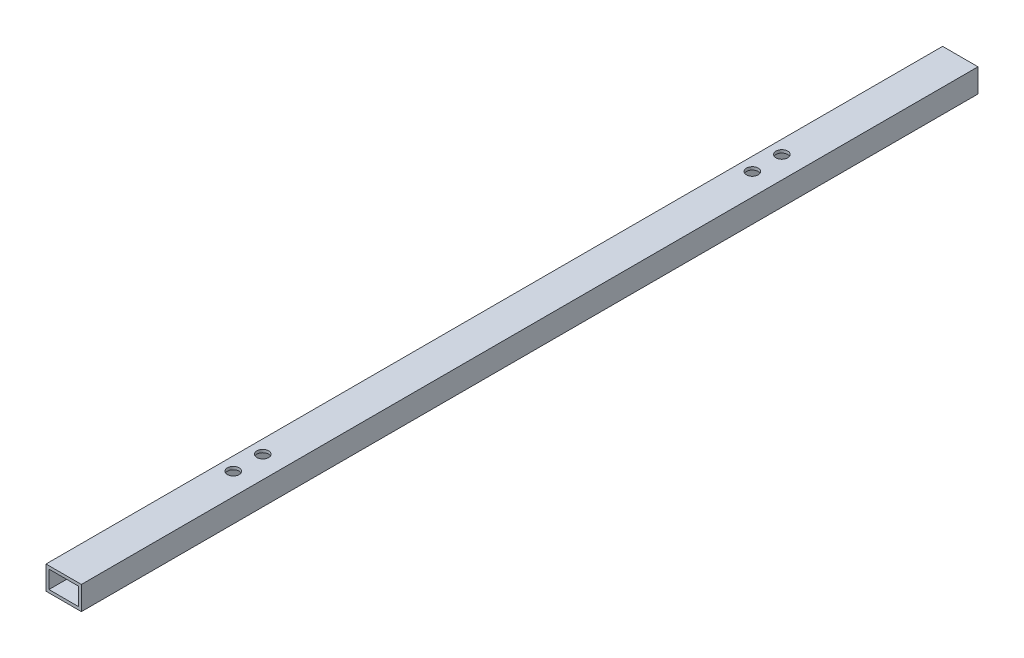
SolidWorks part; units mm, degrees
material "6061 Alloy"
ref_plane "Front Plane" through (0, 0, 0) normal (0, 0, 1) x (1, 0, 0)
ref_plane "Top Plane" through (0, 0, 0) normal (0, 1, 0) x (1, 0, 0)
ref_plane "Right Plane" through (0, 0, 0) normal (1, 0, 0) x (0, 0, -1)
sketch "Sketch1" plane through (0, 0, 0) normal (0, 0, 1) x (1, 0, 0)
  line L0 (19.05, 0) -> (15.875, 0) construction
  line L1 (-19.05, 0) -> (19.05, 0) construction
  line L2 (0, 12.7) -> (0, -12.7)
  point P7 (0, 0)
sketch "Sketch2" plane through (0, 0, 0) normal (1, 0, 0) x (0, 0, -1)
  line L0 (482.6, 0) -> (-482.6, 0)
  point P4 (0, 0)
  dimension "Length" = 965.2
sketch "Sketch3" plane through (0, 0, 0) normal (0, 0, 1) x (1, 0, 0)
  line L0 (-19.05, 0) -> (19.05, 0) construction
  line L5 (19.05, -12.7) -> (-19.05, -12.7)
  line L6 (19.05, -12.7) -> (19.05, 12.7)
  line L11 (19.05, 12.7) -> (-19.05, 12.7)
  line L12 (-19.05, -12.7) -> (-19.05, 12.7)
  line L14 (19.05, -12.7) -> (-19.05, 12.7) construction
  line L15 (19.05, 12.7) -> (-19.05, -12.7) construction
  line L16 (15.875, -9.525) -> (-15.875, -9.525)
  line L17 (15.875, -9.525) -> (15.875, 9.525)
  line L18 (15.875, 9.525) -> (-15.875, 9.525)
  line L19 (-15.875, -9.525) -> (-15.875, 9.525)
  line L20 (15.875, -9.525) -> (-15.875, 9.525) construction
  line L21 (15.875, 9.525) -> (-15.875, -9.525) construction
  point P0 (0, 0)
  point P5 (0, 0)
  point P13 (15.875, -12.7)
  dimension "D1" = 3.175
  dimension "D3" = 38.1
  dimension "D4" = 25.4
  dimension "D2" = 3.175
extrude "Boss-Extrude1" add sketch "Sketch3" along normal up to vertex (482.6 mm away) and the other way up to vertex (482.6 mm away) up to point (0, 0, 482.6) other way up to point (0, 0, -482.6)
sketch "Sketch5" plane through (0, 0, 0) normal (1, 0, 0) x (0, 0, -1)
  line L0 (-482.6, 0) -> (482.6, 0) construction
  line L3 (-482.6, -12.7) -> (-482.6, 12.7) construction
  line L4 (482.6, -12.7) -> (482.6, 12.7) construction
  point P6 (-439.7375, 0)
  point P7 (-425.45, 0)
  point P8 (425.45, 0)
  point P10 (439.7375, 0)
  dimension "D1" = 42.8625
  dimension "D2" = 57.15
  dimension "D3" = 42.8625
  dimension "D4" = 57.15
sketch "Sketch6" plane through (0, 12.7, 0) normal (0, 1, 0) x (1, 0, 0)
  line L0 (19.05, 482.6) -> (-19.05, 482.6) construction
  line L1 (-19.05, 0) -> (19.05, 0) construction
  line L2 (-19.05, -482.6) -> (-19.05, 482.6) construction
  line L3 (19.05, -482.6) -> (19.05, 482.6) construction
  line L4 (-15.875, -482.6) -> (-15.875, 482.6)
  line L5 (-15.875, -482.6) -> (-15.875, 482.6)
  line L6 (-15.875, 279.4) -> (6.35, 279.4) construction
  line L7 (6.35, -482.6) -> (6.35, 482.6)
  line L8 (6.35, -482.6) -> (6.35, 482.6)
  line L9 (-4.7625, 279.4) -> (-4.7625, 311.15) construction
  circle A0 centre (-4.7625, 295.275) radius 6.35
  circle A1 centre (-4.7625, 263.525) radius 6.35
  circle A2 centre (-4.7625, -295.275) radius 6.35
  circle A3 centre (-4.7625, -263.525) radius 6.35
  dimension "D1" = 203.2
  dimension "D4" = 31.75
  dimension "D2" = 3.175
  dimension "D3" = 12.7
extrude "Cut-Extrude1" cut sketch "Sketch6" against normal through all contours A3 | A2 | A0 | A1
equation "\"D1@Sketch3\"=\"Wall thickness@Sketch1\""
equation "\"D1@Sketch5\"=\"Width@Sketch1\"*1.125"
equation "\"D2@Sketch5\"=\"Width@Sketch1\"*1.5"
equation "\"D3@Sketch5\"=\"D1@Sketch5\""
equation "\"D4@Sketch5\"=\"D2@Sketch5\""
equation "\"D2@Sketch3\"=\"Wall Thickness@Sketch1\""
